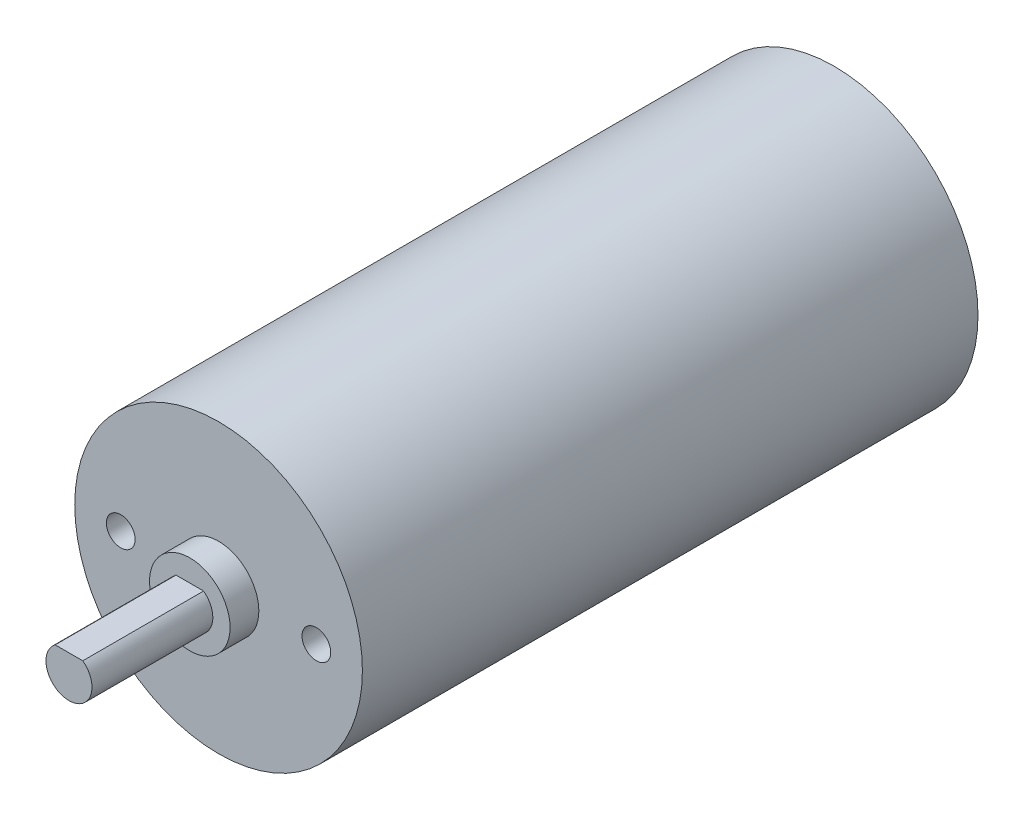
SolidWorks part; units mm, degrees
ref_plane "Front Plane" through (0, 0, 0) normal (0, 0, 1) x (1, 0, 0)
ref_plane "Top Plane" through (0, 0, 0) normal (0, 1, 0) x (1, 0, 0)
ref_plane "Right Plane" through (0, 0, 0) normal (1, 0, 0) x (0, 0, -1)
sketch "Sketch1" plane through (0, 0, 0) normal (0, 0, 1) x (1, 0, 0)
  circle A0 centre (0, 0) radius 12.5
  circle A1 centre (0, 0) radius 8.5 construction
  circle A2 centre (-8.5, 0) radius 1.25
  circle A3 centre (8.5, 0) radius 1.25
  dimension "D1" = 25
  dimension "D2" = 17
  dimension "D3" = 2.5
  dimension "D4" = 2.5
extrude "Boss-Extrude1" add sketch "Sketch1" along normal blind 53.5
sketch "Sketch2" plane through (0, 0, 53.5) normal (0, 0, 1) x (1, 0, 0)
  circle A0 centre (0, 0) radius 3.5
  dimension "D1" = 7
extrude "Boss-Extrude2" add sketch "Sketch2" along normal blind 2.5
sketch "Sketch3" plane through (0, 0, 56) normal (0, 0, 1) x (1, 0, 0)
  line L0 (-1.2, 1.6) -> (1.2, 1.6)
  arc A0 (-1.2, 1.6) -> (1.2, 1.6) centre (0, 0) ccw
  point P1 (0, -2)
  dimension "D1" = 4
  dimension "D2" = 3.6
extrude "Boss-Extrude3" add sketch "Sketch3" along normal blind 10.5
